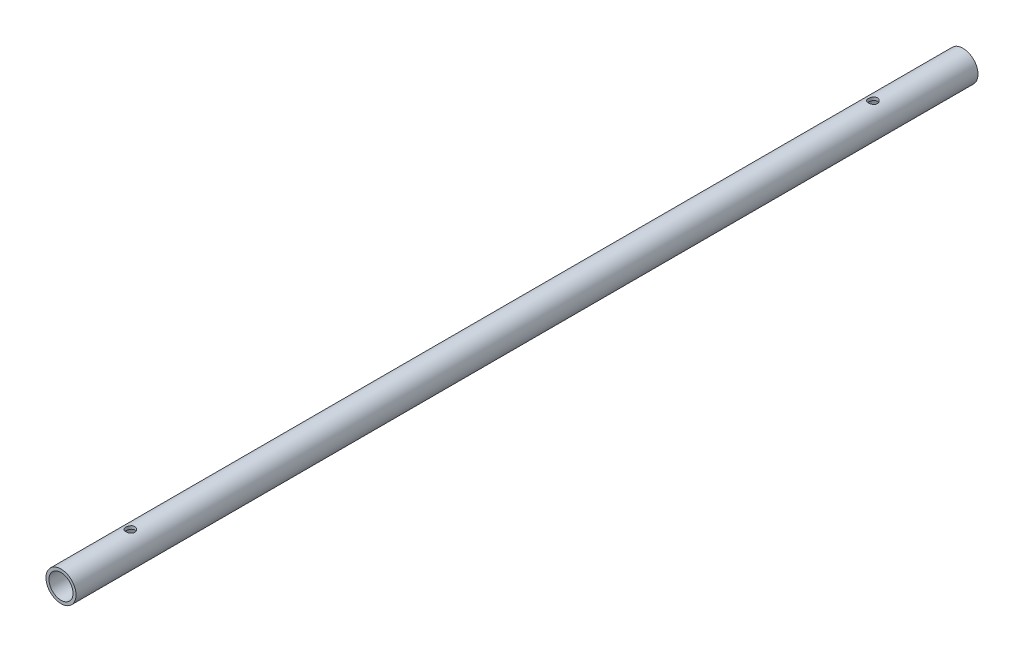
SolidWorks part; units mm, degrees
material "Thornel Mat VMA"
ref_plane "前视基准面" through (0, 0, 0) normal (0, 0, 1) x (1, 0, 0)
ref_plane "上视基准面" through (0, 0, 0) normal (0, 1, 0) x (1, 0, 0)
ref_plane "右视基准面" through (0, 0, 0) normal (1, 0, 0) x (0, 0, -1)
other "Configuration Table"
sketch "草图1" plane through (0, 0, 0) normal (0, 0, 1) x (1, 0, 0)
  circle A0 centre (0, 0) radius 5
  circle A1 centre (0, 0) radius 4
  dimension "D1" = 10
  dimension "D2" = 1
extrude "凸台-拉伸1" add sketch "草图1" along normal blind 300
sketch "草图2" plane through (0, 0, 0) normal (0, 1, 0) x (1, 0, 0)
  line L0 (5, -300) -> (5, 0) construction
  line L1 (-5, -300) -> (5, -300) construction
  circle A0 centre (0, -277) radius 1.5
  circle A1 centre (0, -30) radius 1.5
  dimension "D1" = 3
  dimension "D5" = 3
  dimension "D2" = 5
  dimension "D3" = 23
  dimension "D4" = 30
extrude "切除-拉伸1" cut sketch "草图2" along normal through all
